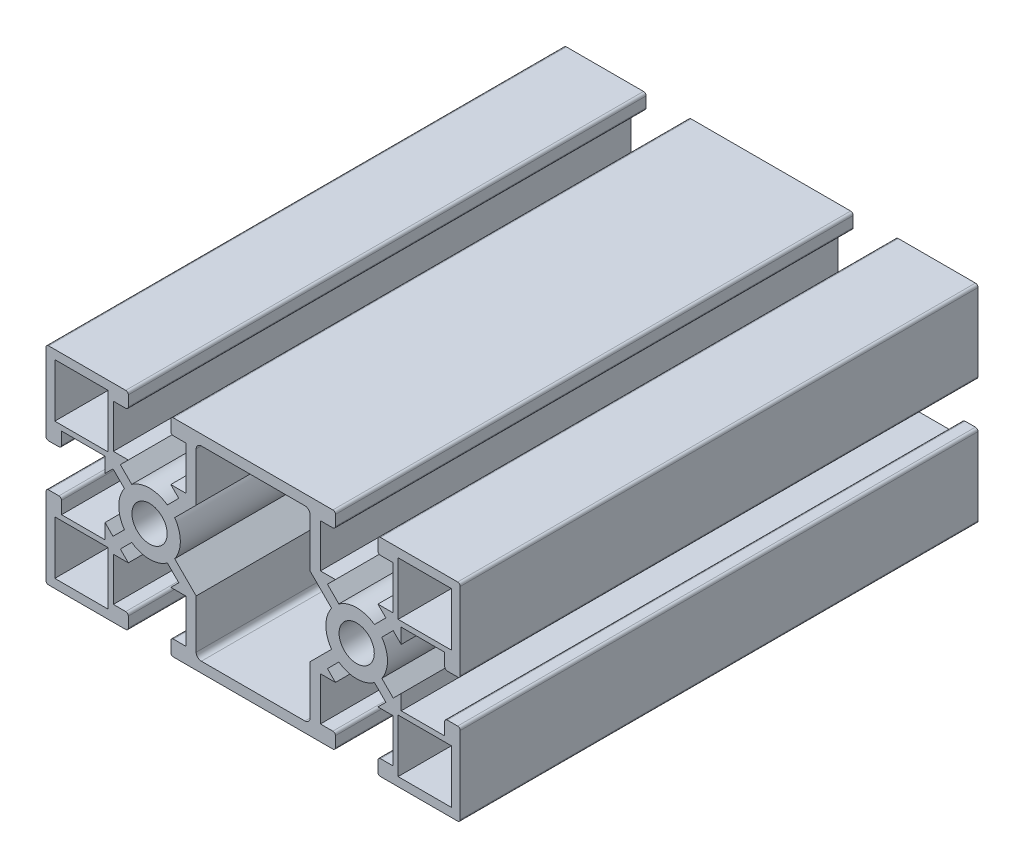
SolidWorks part; units mm, degrees
ref_plane "前视基准面" through (0, 0, 0) normal (0, 0, 1) x (1, 0, 0)
ref_plane "上视基准面" through (0, 0, 0) normal (0, 1, 0) x (1, 0, 0)
ref_plane "右视基准面" through (0, 0, 0) normal (1, 0, 0) x (0, 0, -1)
sketch "草图1" plane through (0, 0, 0) normal (0, 0, 1) x (1, 0, 0)
  line L0 (-26.3632, 19.057) -> (-36.6632, 19.057)
  line L1 (-36.6632, 19.057) -> (-36.6632, 8.757)
  line L2 (-22.4632, 9.357) -> (-25.3632, 9.357)
  line L3 (-35.3632, 7.757) -> (-35.3632, 5.357)
  line L4 (-35.8632, 4.857) -> (-37.8632, 4.857)
  line L5 (-38.3632, 5.357) -> (-38.3632, 20.257)
  line L6 (-37.8632, 20.757) -> (-22.9632, 20.757)
  line L7 (-22.4632, 20.257) -> (-22.4632, 18.257)
  line L8 (-22.9632, 17.757) -> (-25.3632, 17.757)
  line L9 (-26.9632, 7.757) -> (-26.9632, 4.857)
  line L10 (-35.3632, 7.757) -> (-26.9632, 7.757)
  line L11 (-36.6632, 8.757) -> (-26.3632, 8.757)
  line L12 (-25.3632, 17.757) -> (-25.3632, 9.357)
  line L13 (-26.3632, 19.057) -> (-26.3632, 8.757)
  line L14 (-25.4203, 6.3999) -> (-23.2177, 4.1973)
  line L15 (-24.0061, 7.8141) -> (-21.8035, 5.6116)
  line L16 (-26.9632, 4.857) -> (-25.4203, 6.3999)
  line L17 (-24.0061, 7.8141) -> (-22.4632, 9.357)
  line L18 (-14.2632, 9.357) -> (-11.3632, 9.357)
  line L19 (1.1368, 20.757) -> (-13.7632, 20.757)
  line L20 (-14.2632, 20.257) -> (-14.2632, 18.257)
  line L21 (-13.7632, 17.757) -> (-11.3632, 17.757)
  line L22 (-11.3632, 17.757) -> (-11.3632, 9.357)
  line L23 (-9.3632, 17.757) -> (-9.3632, 8.3428)
  line L24 (-9.3632, 8.3428) -> (-13.5086, 4.1973)
  line L25 (-12.7203, 7.8141) -> (-14.9228, 5.6116)
  line L26 (-12.7203, 7.8141) -> (-14.2632, 9.357)
  line L27 (-26.3632, -17.543) -> (-36.6632, -17.543)
  line L28 (-36.6632, -17.543) -> (-36.6632, -7.243)
  line L29 (-22.4632, -7.843) -> (-25.3632, -7.843)
  line L30 (-35.3632, -6.243) -> (-35.3632, -3.843)
  line L31 (-35.8632, -3.343) -> (-37.8632, -3.343)
  line L32 (-38.3632, -3.843) -> (-38.3632, -18.743)
  line L33 (-37.8632, -19.243) -> (-22.9632, -19.243)
  line L34 (-22.4632, -18.743) -> (-22.4632, -16.743)
  line L35 (-22.9632, -16.243) -> (-25.3632, -16.243)
  line L36 (-26.9632, -6.243) -> (-26.9632, -3.343)
  line L37 (-35.3632, -6.243) -> (-26.9632, -6.243)
  line L38 (-36.6632, -7.243) -> (-26.3632, -7.243)
  line L39 (-25.3632, -16.243) -> (-25.3632, -7.843)
  line L40 (-26.3632, -17.543) -> (-26.3632, -7.243)
  line L41 (-25.4203, -4.8859) -> (-23.2177, -2.6833)
  line L42 (-24.0061, -6.3001) -> (-21.8035, -4.0975)
  line L43 (-26.9632, -3.343) -> (-25.4203, -4.8859)
  line L44 (-24.0061, -6.3001) -> (-22.4632, -7.843)
  line L45 (-14.2632, -7.843) -> (-11.3632, -7.843)
  line L46 (1.1368, -19.243) -> (-13.7632, -19.243)
  line L47 (-14.2632, -18.743) -> (-14.2632, -16.743)
  line L48 (-13.7632, -16.243) -> (-11.3632, -16.243)
  line L49 (-11.3632, -16.243) -> (-11.3632, -7.843)
  line L50 (-9.3632, -6.8288) -> (-13.5086, -2.6833)
  line L51 (-12.7203, -6.3001) -> (-14.9228, -4.0975)
  line L52 (-12.7203, -6.3001) -> (-14.2632, -7.843)
  line L53 (17.5368, 9.357) -> (14.6368, 9.357)
  line L54 (2.1368, 20.757) -> (17.0368, 20.757)
  line L55 (17.5368, 20.257) -> (17.5368, 18.257)
  line L56 (17.0368, 17.757) -> (14.6368, 17.757)
  line L57 (14.6368, 17.757) -> (14.6368, 9.357)
  line L58 (12.6368, 17.757) -> (12.6368, 8.3428)
  line L59 (12.6368, 8.3428) -> (16.7823, 4.1973)
  line L60 (15.9939, 7.8141) -> (18.1965, 5.6116)
  line L61 (15.9939, 7.8141) -> (17.5368, 9.357)
  line L62 (29.6368, 19.057) -> (39.9368, 19.057)
  line L63 (39.9368, 19.057) -> (39.9368, 8.757)
  line L64 (25.7368, 9.357) -> (28.6368, 9.357)
  line L65 (38.6368, 7.757) -> (38.6368, 5.357)
  line L66 (39.1368, 4.857) -> (41.1368, 4.857)
  line L67 (41.6368, 5.357) -> (41.6368, 20.257)
  line L68 (41.1368, 20.757) -> (26.2368, 20.757)
  line L69 (25.7368, 20.257) -> (25.7368, 18.257)
  line L70 (26.2368, 17.757) -> (28.6368, 17.757)
  line L71 (30.2368, 7.757) -> (30.2368, 4.857)
  line L72 (38.6368, 7.757) -> (30.2368, 7.757)
  line L73 (39.9368, 8.757) -> (29.6368, 8.757)
  line L74 (28.6368, 17.757) -> (28.6368, 9.357)
  line L75 (29.6368, 19.057) -> (29.6368, 8.757)
  line L76 (28.6939, 6.3999) -> (26.4914, 4.1973)
  line L77 (27.2797, 7.8141) -> (25.0772, 5.6116)
  line L78 (30.2368, 4.857) -> (28.6939, 6.3999)
  line L79 (27.2797, 7.8141) -> (25.7368, 9.357)
  line L80 (17.5368, -7.843) -> (14.6368, -7.843)
  line L81 (2.1368, -19.243) -> (17.0368, -19.243)
  line L82 (17.5368, -18.743) -> (17.5368, -16.743)
  line L83 (17.0368, -16.243) -> (14.6368, -16.243)
  line L84 (14.6368, -16.243) -> (14.6368, -7.843)
  line L85 (12.6368, -6.8288) -> (16.7823, -2.6833)
  line L86 (15.9939, -6.3001) -> (18.1965, -4.0975)
  line L87 (15.9939, -6.3001) -> (17.5368, -7.843)
  line L88 (29.6368, -17.543) -> (39.9368, -17.543)
  line L89 (39.9368, -17.543) -> (39.9368, -7.243)
  line L90 (25.7368, -7.843) -> (28.6368, -7.843)
  line L91 (38.6368, -6.243) -> (38.6368, -3.843)
  line L92 (39.1368, -3.343) -> (41.1368, -3.343)
  line L93 (41.6368, -3.843) -> (41.6368, -18.743)
  line L94 (41.1368, -19.243) -> (26.2368, -19.243)
  line L95 (25.7368, -18.743) -> (25.7368, -16.743)
  line L96 (26.2368, -16.243) -> (28.6368, -16.243)
  line L97 (30.2368, -6.243) -> (30.2368, -3.343)
  line L98 (38.6368, -6.243) -> (30.2368, -6.243)
  line L99 (39.9368, -7.243) -> (29.6368, -7.243)
  line L100 (28.6368, -16.243) -> (28.6368, -7.843)
  line L101 (29.6368, -17.543) -> (29.6368, -7.243)
  line L102 (28.6939, -4.8859) -> (26.4914, -2.6833)
  line L103 (27.2797, -6.3001) -> (25.0772, -4.0975)
  line L104 (30.2368, -3.343) -> (28.6939, -4.8859)
  line L105 (27.2797, -6.3001) -> (25.7368, -7.843)
  line L106 (1.1368, 20.757) -> (2.1368, 20.757)
  line L107 (1.1368, -19.243) -> (2.1368, -19.243)
  line L108 (-8.3632, 18.757) -> (11.6368, 18.757)
  line L109 (-9.3632, -16.243) -> (-9.3632, -6.8288)
  line L110 (12.6368, -16.243) -> (12.6368, -6.8288)
  line L111 (-8.3632, -17.243) -> (11.6368, -17.243)
  arc A0 (-35.8632, 4.857) -> (-35.3632, 5.357) centre (-35.8632, 5.357) ccw
  arc A1 (-38.3632, 5.357) -> (-37.8632, 4.857) centre (-37.8632, 5.357) ccw
  arc A2 (-37.8632, 20.757) -> (-38.3632, 20.257) centre (-37.8632, 20.257) ccw
  arc A3 (-22.4632, 20.257) -> (-22.9632, 20.757) centre (-22.9632, 20.257) ccw
  arc A4 (-22.9632, 17.757) -> (-22.4632, 18.257) centre (-22.9632, 18.257) ccw
  arc A6 (-23.2177, 4.1973) -> (-23.2177, -2.6833) centre (-18.3632, 0.757) ccw
  arc A7 (-21.8035, -4.0975) -> (-14.9228, -4.0975) centre (-18.3632, 0.757) ccw
  arc A8 (-13.5086, -2.6833) -> (-13.5086, 4.1973) centre (-18.3632, 0.757) ccw
  arc A9 (-14.9228, 5.6116) -> (-21.8035, 5.6116) centre (-18.3632, 0.757) ccw
  circle A10 centre (-18.3632, 0.757) radius 3.4
  arc A11 (-13.7632, 20.757) -> (-14.2632, 20.257) centre (-13.7632, 20.257) ccw
  arc A12 (-14.2632, 18.257) -> (-13.7632, 17.757) centre (-13.7632, 18.257) ccw
  arc A13 (-35.3632, -3.843) -> (-35.8632, -3.343) centre (-35.8632, -3.843) ccw
  arc A14 (-37.8632, -3.343) -> (-38.3632, -3.843) centre (-37.8632, -3.843) ccw
  arc A15 (-38.3632, -18.743) -> (-37.8632, -19.243) centre (-37.8632, -18.743) ccw
  arc A16 (-22.9632, -19.243) -> (-22.4632, -18.743) centre (-22.9632, -18.743) ccw
  arc A17 (-22.4632, -16.743) -> (-22.9632, -16.243) centre (-22.9632, -16.743) ccw
  arc A18 (-14.2632, -18.743) -> (-13.7632, -19.243) centre (-13.7632, -18.743) ccw
  arc A19 (-13.7632, -16.243) -> (-14.2632, -16.743) centre (-13.7632, -16.743) ccw
  arc A20 (17.5368, 20.257) -> (17.0368, 20.757) centre (17.0368, 20.257) ccw
  arc A21 (17.0368, 17.757) -> (17.5368, 18.257) centre (17.0368, 18.257) ccw
  arc A22 (12.6368, 17.757) -> (11.6368, 18.757) centre (11.6368, 17.757) ccw
  arc A24 (16.7823, 4.1973) -> (16.7823, -2.6833) centre (21.6368, 0.757) ccw
  arc A25 (18.1965, -4.0975) -> (25.0772, -4.0975) centre (21.6368, 0.757) ccw
  arc A26 (26.4914, -2.6833) -> (26.4914, 4.1973) centre (21.6368, 0.757) ccw
  arc A27 (25.0772, 5.6116) -> (18.1965, 5.6116) centre (21.6368, 0.757) ccw
  circle A28 centre (21.6368, 0.757) radius 3.4
  arc A29 (38.6368, 5.357) -> (39.1368, 4.857) centre (39.1368, 5.357) ccw
  arc A30 (41.1368, 4.857) -> (41.6368, 5.357) centre (41.1368, 5.357) ccw
  arc A31 (41.6368, 20.257) -> (41.1368, 20.757) centre (41.1368, 20.257) ccw
  arc A32 (26.2368, 20.757) -> (25.7368, 20.257) centre (26.2368, 20.257) ccw
  arc A33 (25.7368, 18.257) -> (26.2368, 17.757) centre (26.2368, 18.257) ccw
  arc A34 (17.0368, -19.243) -> (17.5368, -18.743) centre (17.0368, -18.743) ccw
  arc A35 (17.5368, -16.743) -> (17.0368, -16.243) centre (17.0368, -16.743) ccw
  arc A36 (39.1368, -3.343) -> (38.6368, -3.843) centre (39.1368, -3.843) ccw
  arc A37 (41.6368, -3.843) -> (41.1368, -3.343) centre (41.1368, -3.843) ccw
  arc A38 (41.1368, -19.243) -> (41.6368, -18.743) centre (41.1368, -18.743) ccw
  arc A39 (25.7368, -18.743) -> (26.2368, -19.243) centre (26.2368, -18.743) ccw
  arc A40 (26.2368, -16.243) -> (25.7368, -16.743) centre (26.2368, -16.743) ccw
  arc A41 (-8.3632, 18.757) -> (-9.3632, 17.757) centre (-8.3632, 17.757) ccw
  arc A42 (-9.3632, -16.243) -> (-8.3632, -17.243) centre (-8.3632, -16.243) ccw
  arc A43 (11.6368, -17.243) -> (12.6368, -16.243) centre (11.6368, -16.243) ccw
extrude "凸台-拉伸1" add sketch "草图1" along normal blind 100
